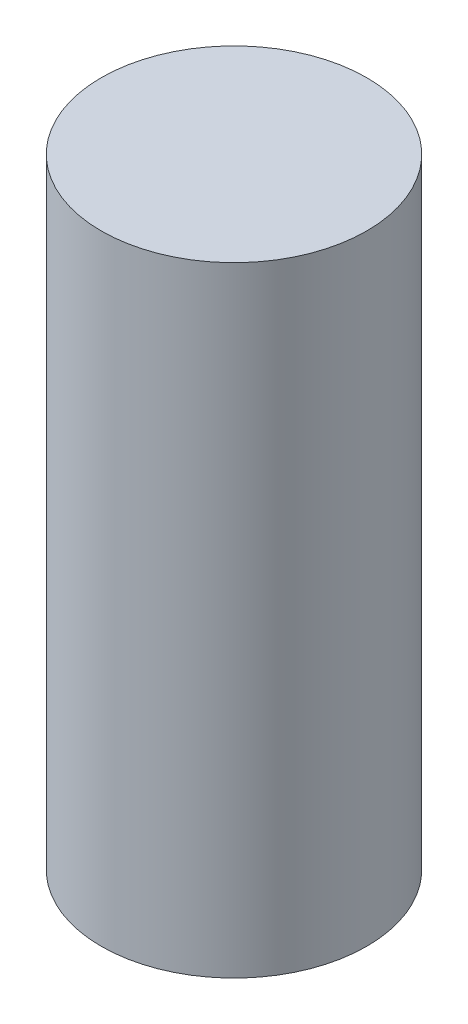
SolidWorks part; units mm, degrees
ref_plane "Front Plane" through (0, 0, 0) normal (0, 0, 1) x (1, 0, 0)
ref_plane "Top Plane" through (0, 0, 0) normal (0, 1, 0) x (1, 0, 0)
ref_plane "Right Plane" through (0, 0, 0) normal (1, 0, 0) x (0, 0, -1)
sketch "ROLLER" plane through (0, 0, 0) normal (0, 1, 0) x (1, 0, 0)
  circle A0 centre (0, 0) radius 1.5
  dimension "D1" = 3
extrude "Body Extrude" add sketch "ROLLER" along normal blind 7
